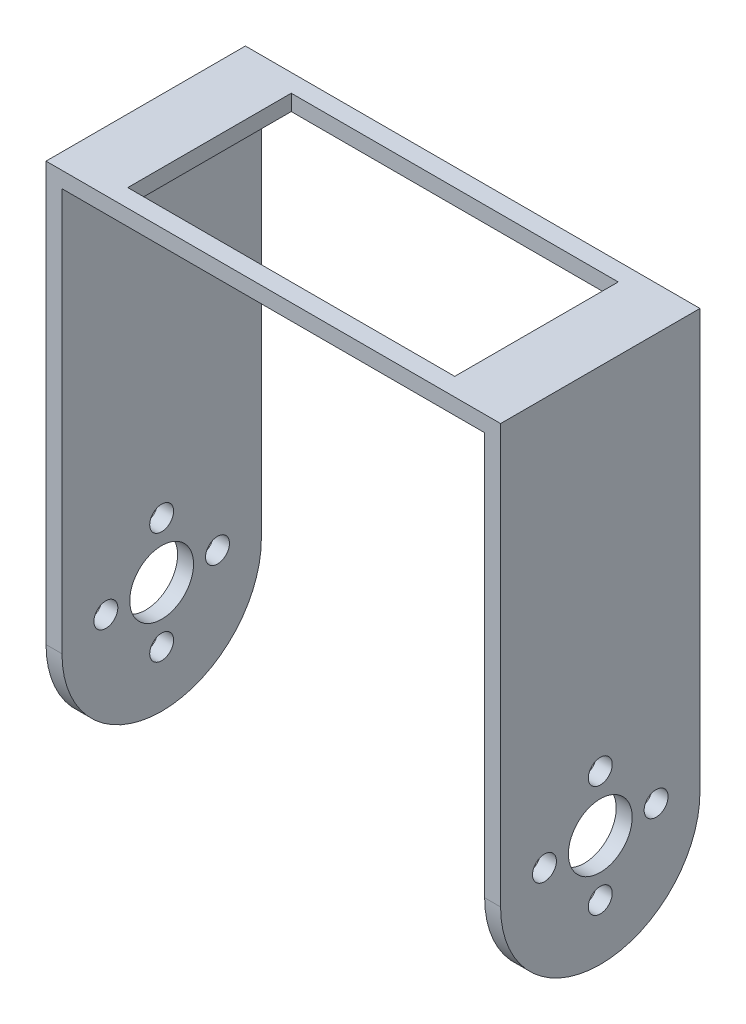
SolidWorks part; units mm, degrees
material "1060 Alloy"
ref_plane "Front Plane" through (0, 0, 0) normal (0, 0, 1) x (1, 0, 0)
ref_plane "Top Plane" through (0, 0, 0) normal (0, 1, 0) x (1, 0, 0)
ref_plane "Right Plane" through (0, 0, 0) normal (1, 0, 0) x (0, 0, -1)
sketch "Sketch3" plane through (0, 0, 0) normal (0, 0, 1) x (1, 0, 0)
  line L0 (-79.9255, 45.3865) -> (-27.043, 45.3865)
  line L1 (-81.9255, 45.3865) -> (-79.9255, 45.3865)
  line L2 (-81.9255, 45.3865) -> (-81.9255, -19.6135)
  line L3 (-81.9255, -19.6135) -> (-79.9255, -19.6135)
  line L4 (-79.9255, 43.39) -> (-79.9255, -19.6135)
  line L5 (-81.9255, 45.3865) -> (-79.9255, -19.6135) construction
  line L6 (-81.9255, -19.6135) -> (-79.9255, 45.3865) construction
  line L7 (-79.9255, 43.39) -> (-26.9255, 43.39)
  line L8 (-26.9255, 43.39) -> (-26.9255, -19.6135)
  line L9 (-27.043, 45.3865) -> (-24.9255, 45.3865)
  line L10 (-26.9255, -19.6135) -> (-24.9255, -19.6135)
  line L11 (-24.9255, 45.3865) -> (-24.9255, -19.6135)
  point P0 (-80.9255, 12.8865)
  dimension "D1" = 65
  dimension "D2" = 2
  dimension "D3" = 2
  dimension "D4" = 57
  dimension "D5" = 2
extrude "Boss-Extrude2" add sketch "Sketch3" along normal blind 25
sketch "Sketch6" plane through (-81.9255, 0, 0) normal (-1, 0, 0) x (0, 0, 1)
  line L1 (25, 45.3865) -> (0, 45.3865) construction
  line L2 (0, 45.3865) -> (0, -19.6135) construction
  circle A0 centre (12.5, -5.6135) radius 4
  dimension "D1" = 51
  dimension "D2" = 12.5
extrude "Cut-Extrude2" cut sketch "Sketch6" against normal through all
sketch "Sketch8" plane through (-81.9255, 0, 0) normal (-1, 0, 0) x (0, 0, 1)
  line L0 (25, 45.3865) -> (25, -19.6135) construction
  line L1 (25, -19.6135) -> (0, -19.6135) construction
  line L2 (0, 45.3865) -> (0, -19.6135) construction
  line L3 (25, -19.6135) -> (0, -19.6135)
  line L4 (0, 45.3865) -> (0, -19.6135)
  line L5 (25, 45.3865) -> (25, -19.6135)
  circle A0 centre (12.5, -7.1135) radius 12.5
  line M4 (0, -19.6135) -> (25, -19.6135)
  line M5 (25, -19.6135) -> (25, 45.3865)
extrude "Cut-Extrude3" cut sketch "Sketch8" against normal through all contours A0 L4 M4 | A0 L3 M5
sketch "Sketch9" plane through (-24.9255, 0, 0) normal (1, 0, 0) x (0, 0, -1)
  line L0 (-12.5, -5.6135) -> (-12.5, 1.3865) construction
  circle A0 centre (-12.5, 1.3865) radius 1.5
  circle A2 centre (-5.5, -5.6135) radius 1.5
  circle A3 centre (-12.5, -12.6135) radius 1.5
  circle A4 centre (-19.5, -5.6135) radius 1.5
  point P12 (-12.5, -5.6135)
  point P13 (-12.5, -5.6135)
  dimension "D1" = 4
extrude "Cut-Extrude4" cut sketch "Sketch9" against normal through all
sketch "Croquis2" plane through (0, 45.3865, 0) normal (0, 1, 0) x (1, 0, 0)
  line L1 (-73.9255, -2.25) -> (-32.9255, -2.25)
  line L2 (-73.9255, -2.25) -> (-73.9255, -22.75)
  line L3 (-73.9255, -22.75) -> (-32.9255, -22.75)
  line L4 (-32.9255, -2.25) -> (-32.9255, -22.75)
  line L5 (-73.9255, -2.25) -> (-32.9255, -22.75) construction
  line L6 (-73.9255, -22.75) -> (-32.9255, -2.25) construction
  point P0 (-53.4255, -12.5)
extrude "Cortar-Extruir1" cut sketch "Croquis2" against normal blind 10
